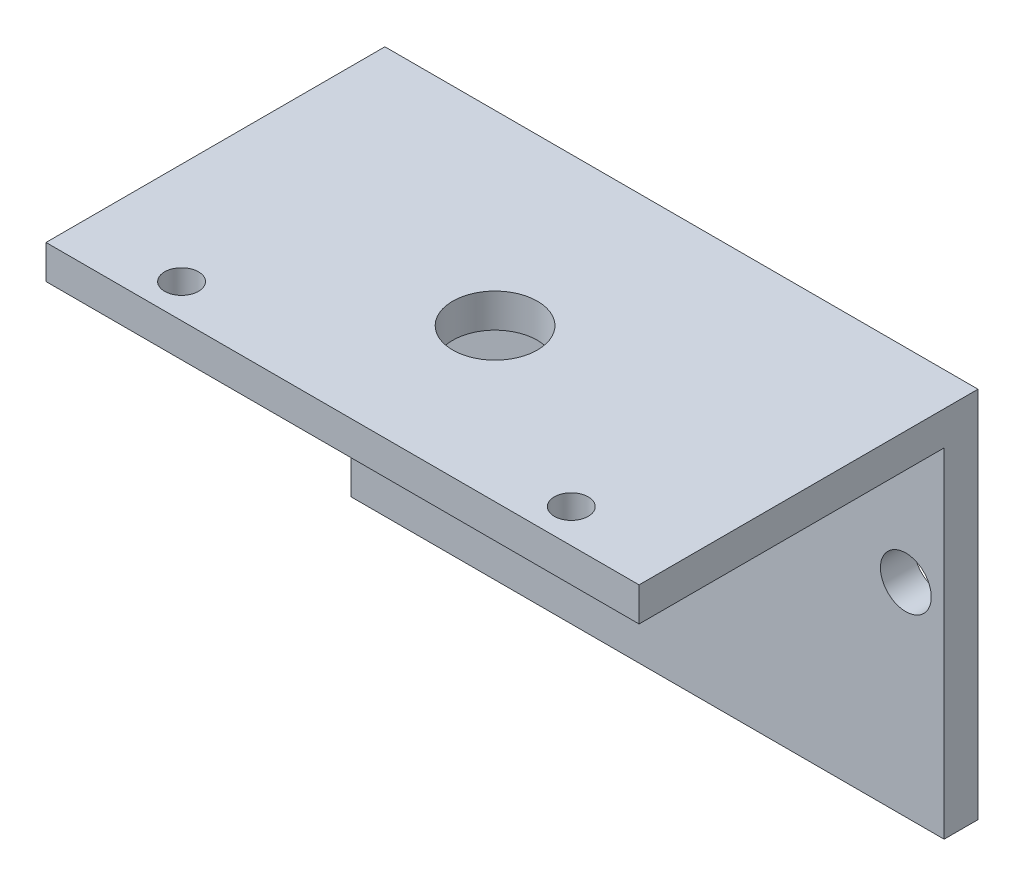
SolidWorks part; units mm, degrees
ref_plane "Front Plane" through (0, 0, 0) normal (0, 0, 1) x (1, 0, 0)
ref_plane "Top Plane" through (0, 0, 0) normal (0, 1, 0) x (1, 0, 0)
ref_plane "Right Plane" through (0, 0, 0) normal (1, 0, 0) x (0, 0, -1)
sketch "Sketch1" plane through (0, 0, 0) normal (0, 1, 0) x (1, 0, 0)
  line L1 (-17.5, -10) -> (17.5, -10)
  line L2 (-17.5, -10) -> (-17.5, 10)
  line L3 (-17.5, 10) -> (17.5, 10)
  line L4 (17.5, -10) -> (17.5, 10)
  line L5 (-17.5, -10) -> (17.5, 10) construction
  line L6 (-17.5, 10) -> (17.5, -10) construction
  point P0 (0, 0)
  point P3 (0, 0)
  dimension "D1" = 20
  dimension "D2" = 35
extrude "Boss-Extrude1" add sketch "Sketch1" along normal blind 2
sketch "Sketch2" plane through (0, 0, 0) normal (0, -1, 0) x (1, 0, 0)
  line L0 (17.5, 10) -> (17.5, -10) construction
  line L1 (-17.5, -10) -> (17.5, -10)
  line L2 (-17.5, -10) -> (-17.5, -8)
  line L3 (-17.5, -8) -> (17.5, -8)
  line L4 (17.5, -10) -> (17.5, -8)
  dimension "D1" = 2
extrude "Boss-Extrude2" add sketch "Sketch2" along normal blind 20
sketch "Sketch3" plane through (0, 0, -10) normal (0, 0, -1) x (-1, 0, 0)
  line L0 (-17.5, 2) -> (17.5, 2) construction
  circle A0 centre (-15.2406, -8) radius 1.5
  circle A1 centre (15.4432, -8) radius 1.5
  point P2 (-13.4166, -9.5076)
  point P5 (-15.2406, -9.3445)
  point P6 (15.4432, -8.8987)
  dimension "D1" = 3
  dimension "D2" = 3
  dimension "D3" = 10
  dimension "D4" = 10
extrude "Cut-Extrude1" cut sketch "Sketch3" against normal blind 20
sketch "Sketch4" plane through (0, 0, 0) normal (0, -1, 0) x (1, 0, 0)
  line L4 (-17.5, 10) -> (17.5, 10) construction
  circle A0 centre (-11.5, 8) radius 1
  circle A1 centre (11.5, 8) radius 1
  point P2 (-13.4571, 5.656)
  point P5 (12.8896, 6.1424)
  point P6 (-14.1056, 8.4107)
  dimension "D1" = 2
  dimension "D2" = 2
  dimension "D3" = 2
  dimension "D4" = 2
extrude "Cut-Extrude2" cut sketch "Sketch4" against normal blind 20
sketch "Sketch6" plane through (0, 0, 0) normal (0, -1, 0) x (1, 0, 0)
  line L1 (-17.5, 10) -> (17.5, 10) construction
  circle A0 centre (0, 1) radius 2.5
  point P4 (0, 10)
  dimension "D1" = 5
  dimension "D2" = 9
extrude "Cut-Extrude3" cut sketch "Sketch6" against normal blind 20
